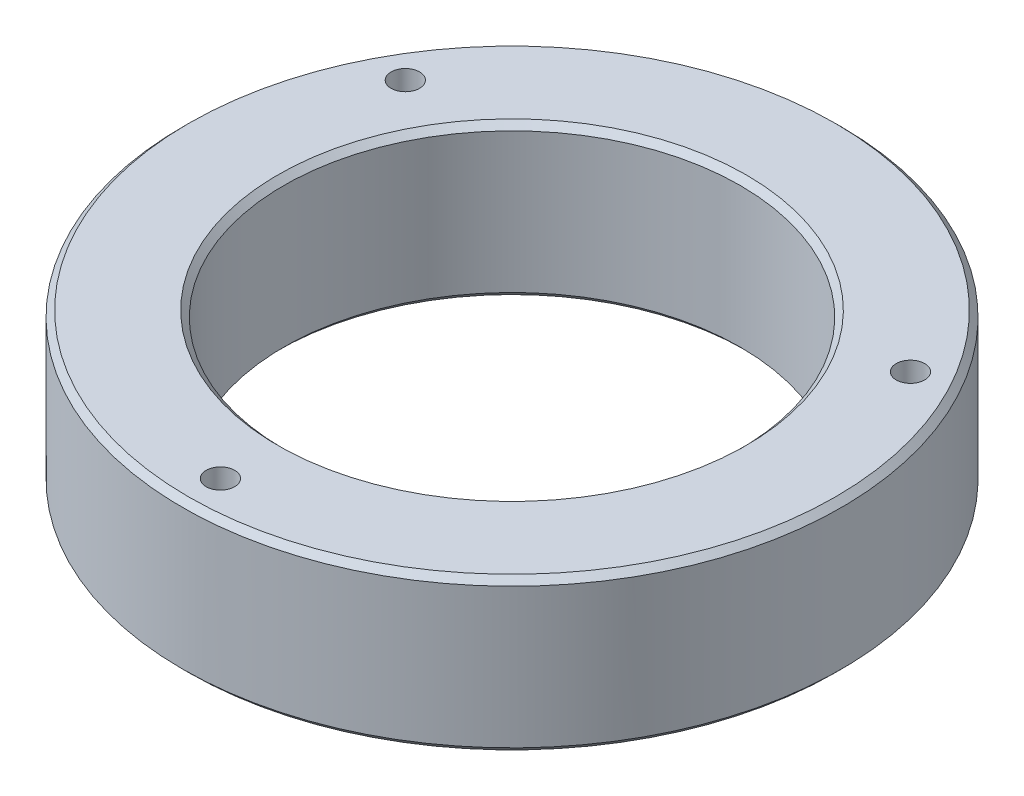
SolidWorks part; units mm, degrees
ref_plane "Front Plane" through (0, 0, 0) normal (1, 0, 0) x (0, 1, 0)
ref_plane "Top Plane" through (0, 0, 0) normal (0, 0, 1) x (0, 1, 0)
ref_plane "Right Plane" through (0, 0, 0) normal (0, 1, 0) x (-1, 0, 0)
sketch "Sketch1" plane through (0, 0, 0) normal (0, 0, 1) x (0, 1, 0)
  line L0 (-19.05, 82.5246) -> (19.05, 82.5246)
  line L1 (19.05, 82.5246) -> (19.05, 57.15)
  line L2 (19.05, 57.15) -> (-19.05, 57.15)
  line L3 (-19.05, 57.15) -> (-19.05, 82.5246)
  line L4 (-44.45, 0) -> (44.45, 0) construction
  point P6 (0, 0)
  dimension "D1" = 38.1
  dimension "D2" = 25.3746
  dimension "D3" = 82.5246
  dimension "D4" = 19.05
revolve "Revolve1" add sketch "Sketch1" angle 360 about L4
chamfer "Chamfer1" distance 1.524 angle 45 4 edges at (0, 19.05, -57.15) (0, -19.05, -57.15) (0, 19.05, -82.5246) (0, -19.05, -82.5246)
hole_wizard "CBORE for 1/4 Socket Head Cap Screw1" positions "Sketch3" profile "Sketch2" counterbore size "1/4" standard "ANSI Inch"
sketch "Sketch3" plane through (0, -19.05, 0) normal (0, -1, 0) x (-1, 0, 0)
  circle A0 centre (0, 0.0068) radius 73.0318 construction
  circle A1 centre (0, 0) radius 58.674 construction
  point P0 (0, -73.025)
  point P1 (-63.246, 36.5252)
  point P3 (63.246, 36.5252)
  dimension "D1" = 146.0637
  dimension "D2" = 63.246
  dimension "D3" = 63.246
  dimension "D4" = 0.0068
  dimension "D5" = 36.5252
  dimension "D6" = 73.025
sketch "Sketch2" plane through (0, -19.05, 73.025) normal (1, 0, 0) x (0, 0, -1)
  line L0 (0, 0) -> (0, 40.2443)
  line L1 (0, 40.2443) -> (3.5687, 38.1)
  line L2 (3.5687, 38.1) -> (3.5687, 9.652)
  line L3 (3.5687, 9.652) -> (5.5626, 9.652)
  line L4 (5.5626, 9.652) -> (5.5626, 0)
  line L5 (5.5626, 0) -> (0, 0)
  line L10 (0, 40.2443) -> (-3.5687, 38.1) construction
  line L11 (0, -6.35) -> (0, 107.95) construction
  dimension "Hole Dia." = 7.1374
  dimension "Hole Depth" = 38.1
  dimension "C'Bore Dia." = 11.1252
  dimension "C'Bore Depth" = 9.652
  dimension "Drill Angle" = 118
hole_wizard "3/8-16 Tapped Hole2" positions "Sketch7" profile "Sketch6" tap size "3/8-16" standard "ANSI Inch"
sketch "Sketch7" plane through (0, -19.05, 0) normal (0, -1, 0) x (-1, 0, 0)
  circle A0 centre (0, -73.025) radius 5.5626 construction
  point P0 (-69.85, 0)
  point P1 (69.85, 0)
  dimension "D1" = 69.85
  dimension "D2" = 69.85
  dimension "D3" = 73.025
  dimension "D4" = 73.025
sketch "Sketch6" plane through (69.85, -19.05, 0) normal (1, 0, 0) x (0, 0, -1)
  line L0 (0, 0) -> (0, 27.7847)
  line L1 (0, 27.7847) -> (3.9687, 25.4)
  line L2 (3.9687, 25.4) -> (3.9687, 0)
  line L5 (3.9687, 0) -> (0, 0)
  line L10 (0, 27.7847) -> (-3.9687, 25.4) construction
  line L11 (0, -6.35) -> (0, 107.95) construction
  dimension "Tap Drill Dia." = 7.9375
  dimension "Tap Drill Depth" = 25.4
  dimension "Drill Angle" = 118
cosmetic thread "Hole Thread3"
cosmetic thread "Hole Thread4"
